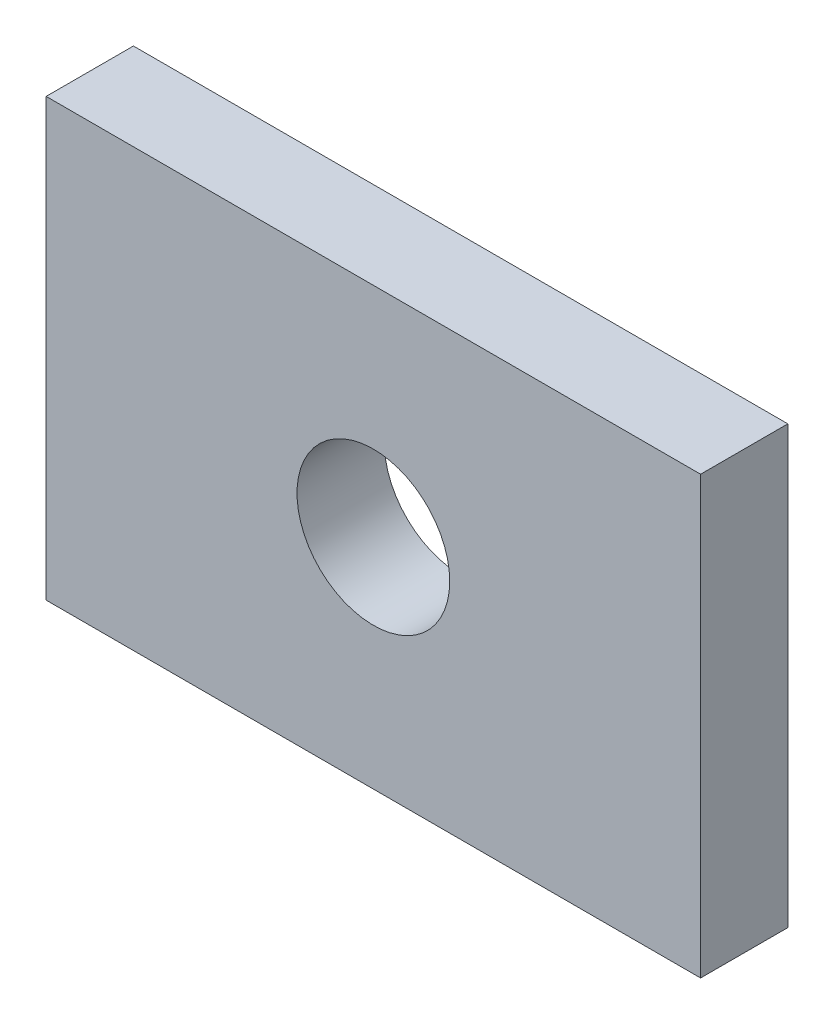
SolidWorks part; units mm, degrees
ref_plane "Plan de face" through (0, 0, 0) normal (0, 0, 1) x (1, 0, 0)
ref_plane "Plan de dessus" through (0, 0, 0) normal (0, 1, 0) x (1, 0, 0)
ref_plane "Plan de droite" through (0, 0, 0) normal (1, 0, 0) x (0, 0, -1)
sketch "Esquisse2" plane through (0, 0, 0) normal (0, 0, 1) x (1, 0, 0)
  line L1 (-7.5, 5) -> (7.5, 5)
  line L2 (-7.5, 5) -> (-7.5, -5)
  line L3 (-7.5, -5) -> (7.5, -5)
  line L4 (7.5, 5) -> (7.5, -5)
  circle A0 centre (0, 0) radius 1.75
  dimension "D1" = 3.5
  dimension "D2" = 7.5
  dimension "D3" = 5
  dimension "D4" = 15
  dimension "D5" = 10
extrude "Boss.-Extru.1" add sketch "Esquisse2" along normal blind 2
